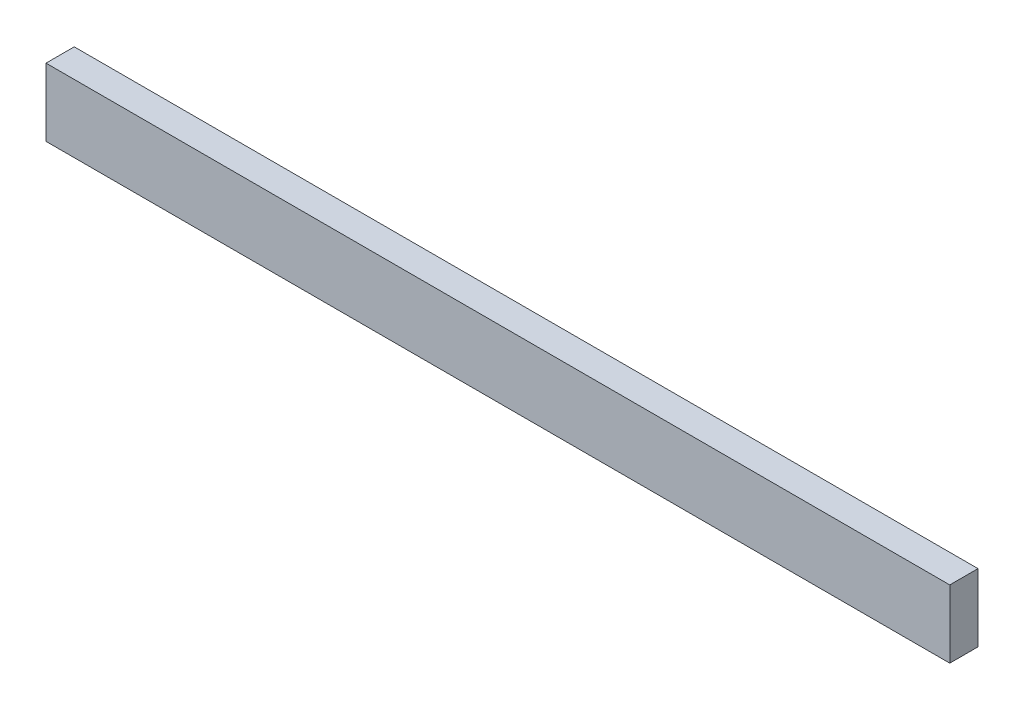
SolidWorks part; units mm, degrees
ref_plane "Plan de face" through (0, 0, 0) normal (0, 0, 1) x (1, 0, 0)
ref_plane "Plan de dessus" through (0, 0, 0) normal (0, 1, 0) x (1, 0, 0)
ref_plane "Plan de droite" through (0, 0, 0) normal (1, 0, 0) x (0, 0, -1)
sketch "Esquisse1" plane through (0, 0, 0) normal (0, 0, 1) x (1, 0, 0)
  line L1 (0, 0) -> (800, 0)
  line L2 (0, 0) -> (0, 60)
  line L3 (0, 60) -> (800, 60)
  line L4 (800, 0) -> (800, 60)
  dimension "D1" = 60
  dimension "D2" = 800
extrude "Boss.-Extru.1" add sketch "Esquisse1" along normal blind 25
